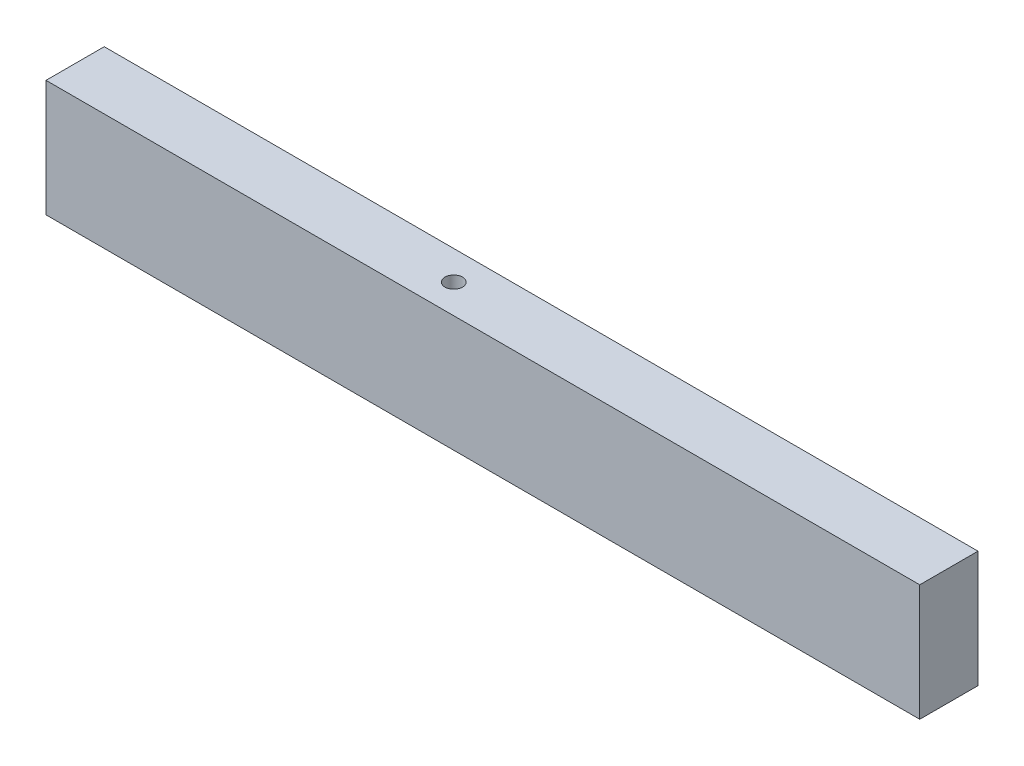
SolidWorks part; units mm, degrees
ref_plane "Front" through (0, 0, 0) normal (0, 0, 1) x (1, 0, 0)
ref_plane "Top" through (0, 0, 0) normal (0, 1, 0) x (1, 0, 0)
ref_plane "Right" through (0, 0, 0) normal (1, 0, 0) x (0, 0, -1)
sketch "Skizze1" plane through (0, 0, 0) normal (1, 0, 0) x (0, 0, -1)
  line L1 (-10, -20) -> (10, -20)
  line L2 (-10, -20) -> (-10, 20)
  line L3 (-10, 20) -> (10, 20)
  line L4 (10, -20) -> (10, 20)
  line L5 (-10, -20) -> (10, 20) construction
  line L6 (-10, 20) -> (10, -20) construction
  point P0 (0, 0)
  dimension "D1" = 20
  dimension "D2" = 40
extrude "Aufsatz-Linear austragen1" add sketch "Skizze1" along normal blind 300
sketch "Skizze2" plane through (0, 20, 0) normal (0, 1, 0) x (1, 0, 0)
  line L0 (0, 0) -> (300, 0) construction
  line L1 (0, 10) -> (0, -10) construction
  line L2 (300, 10) -> (300, -10) construction
  line L3 (150, 0) -> (150, 10) construction
  line L4 (300, 10) -> (0, 10) construction
  circle A0 centre (130, 0) radius 3
  circle A2 centre (114, 0) radius 3 construction
  circle A3 centre (202, 0) radius 3 construction
  dimension "D2" = 6
  dimension "130" = 130
  dimension "D3" = 114
  dimension "D4" = 202
extrude "Schnitt-Linear austragen1" cut sketch "Skizze2" against normal through all
